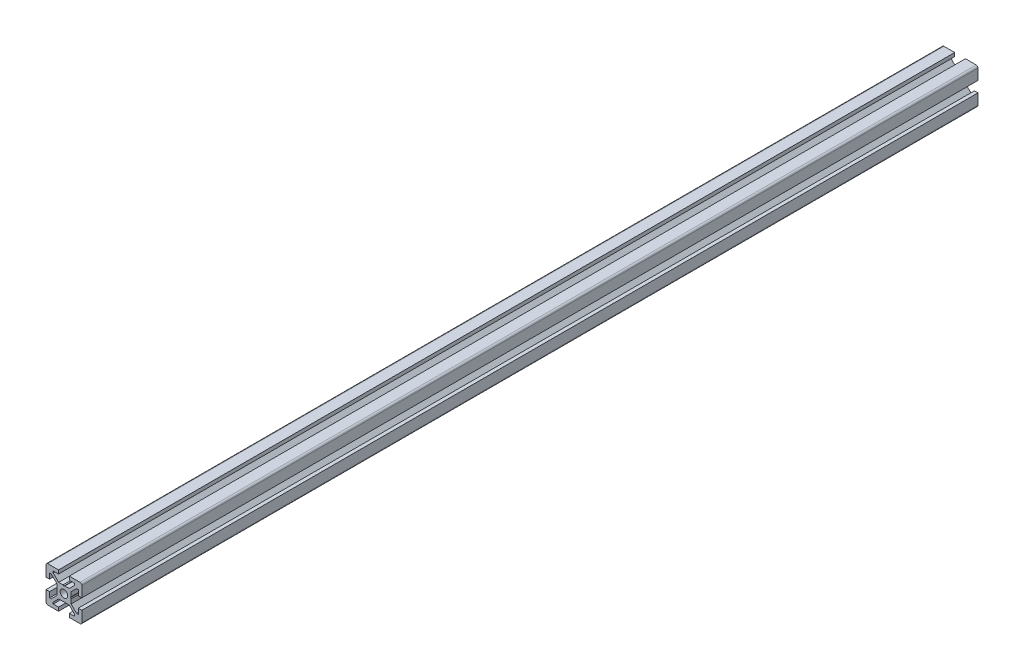
SolidWorks part; units mm, degrees
ref_plane "Front Plane" through (0, 0, 0) normal (0, 0, 1) x (1, 0, 0)
ref_plane "Top Plane" through (0, 0, 0) normal (0, 1, 0) x (1, 0, 0)
ref_plane "Right Plane" through (0, 0, 0) normal (1, 0, 0) x (0, 0, -1)
ref_plane "Plane1" through (0, 0, 0) normal (0, 0, 1) x (1, 0, 0)
sketch "Sketch1" plane through (0, 0, 0) normal (0, 0, 1) x (1, 0, 0)
  line L0 (-10, -3) -> (-10, -9)
  line L1 (-9, -10) -> (-3, -10)
  line L2 (-3, -10) -> (-3, -8)
  line L3 (-3, -8) -> (-6, -8)
  line L4 (-6, -8) -> (-6, -7.0607)
  line L5 (-6, -7.0607) -> (-2.9393, -4)
  line L6 (-2.9393, -4) -> (-0.5196, -4)
  line L7 (-0.5196, -4) -> (0, -3.7)
  line L8 (0, -3.7) -> (0.5196, -4)
  line L9 (0.5196, -4) -> (2.9393, -4)
  line L10 (2.9393, -4) -> (6, -7.0607)
  line L11 (6, -7.0607) -> (6, -8)
  line L12 (6, -8) -> (3, -8)
  line L13 (3, -8) -> (3, -10)
  line L14 (3, -10) -> (9, -10)
  line L15 (10, -9) -> (10, -3)
  line L16 (10, -3) -> (8, -3)
  line L17 (8, -3) -> (8, -6)
  line L18 (8, -6) -> (7.0607, -6)
  line L19 (7.0607, -6) -> (4, -2.9393)
  line L20 (4, -2.9393) -> (4, -0.5196)
  line L21 (4, -0.5196) -> (3.7, 0)
  line L22 (3.7, 0) -> (4, 0.5196)
  line L23 (4, 0.5196) -> (4, 2.9393)
  line L24 (4, 2.9393) -> (7.0607, 6)
  line L25 (7.0607, 6) -> (8, 6)
  line L26 (8, 6) -> (8, 3)
  line L27 (8, 3) -> (10, 3)
  line L28 (10, 3) -> (10, 9)
  line L29 (9, 10) -> (3, 10)
  line L30 (3, 10) -> (3, 8)
  line L31 (3, 8) -> (6, 8)
  line L32 (6, 8) -> (6, 7.0607)
  line L33 (6, 7.0607) -> (2.9393, 4)
  line L34 (2.9393, 4) -> (0.5196, 4)
  line L35 (0.5196, 4) -> (0, 3.7)
  line L36 (0, 3.7) -> (-0.5196, 4)
  line L37 (-0.5196, 4) -> (-2.9393, 4)
  line L38 (-2.9393, 4) -> (-6, 7.0607)
  line L39 (-6, 7.0607) -> (-6, 8)
  line L40 (-6, 8) -> (-3, 8)
  line L41 (-3, 8) -> (-3, 10)
  line L42 (-3, 10) -> (-9, 10)
  line L43 (-10, 9) -> (-10, 3)
  line L44 (-10, 3) -> (-8, 3)
  line L45 (-8, 3) -> (-8, 6)
  line L46 (-8, 6) -> (-7.0607, 6)
  line L47 (-7.0607, 6) -> (-4, 2.9393)
  line L48 (-4, 2.9393) -> (-4, 0.5196)
  line L49 (-4, 0.5196) -> (-3.7, 0)
  line L50 (-3.7, 0) -> (-4, -0.5196)
  line L51 (-4, -0.5196) -> (-4, -2.9393)
  line L52 (-4, -2.9393) -> (-7.0607, -6)
  line L53 (-7.0607, -6) -> (-8, -6)
  line L54 (-8, -6) -> (-8, -3)
  line L55 (-8, -3) -> (-10, -3)
  arc A0 (-10, -9) -> (-9, -10) centre (-9, -9) ccw
  arc A1 (9, -10) -> (10, -9) centre (9, -9) ccw
  arc A2 (10, 9) -> (9, 10) centre (9, 9) ccw
  arc A3 (-9, 10) -> (-10, 9) centre (-9, 9) ccw
extrude "Boss-Extrude1" add sketch "Sketch1" against normal blind 500
ref_plane "Plane2" through (0, 0, 0) normal (1, 0, 0) x (0, 0, -1)
sketch "Sketch2" plane through (0, 0, 0) normal (1, 0, 0) x (0, 0, -1)
  line L0 (0, 0) -> (0, 2.1)
  line L1 (0, 2.1) -> (500, 2.1)
  line L2 (500, 2.1) -> (500, 0)
  line L3 (500, 0) -> (0, 0)
  line L4 (500, 0) -> (0, 0) construction
revolve "Cut-Revolve1" cut sketch "Sketch2" angle 360 about L4
